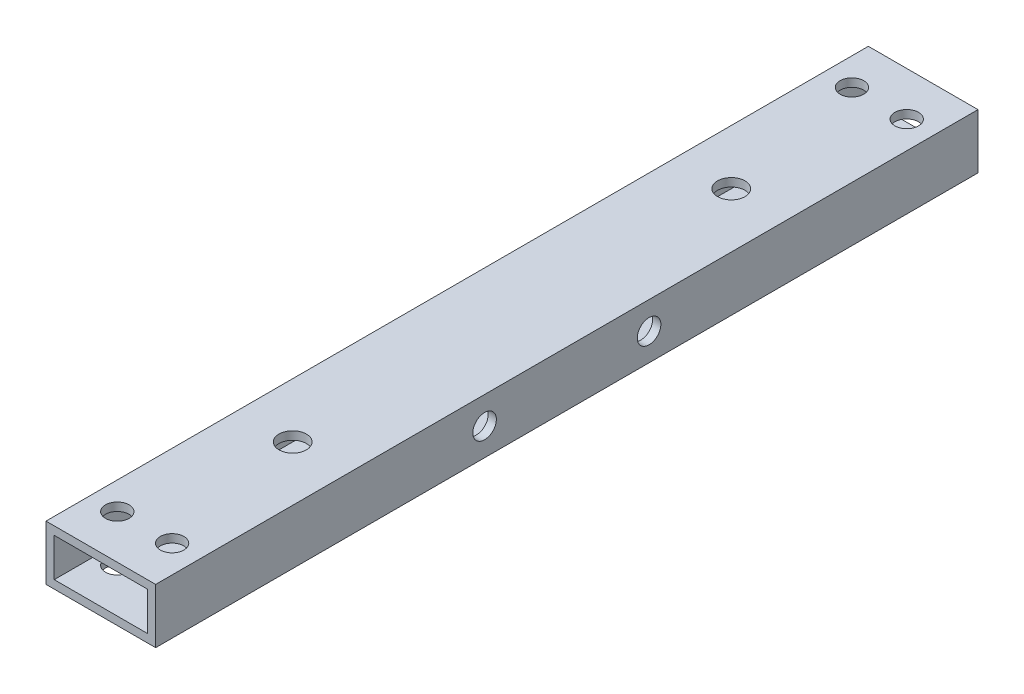
SolidWorks part; units mm, degrees
material "5052-H34"
ref_plane "正面" through (0, 0, 0) normal (0, 0, 1) x (1, 0, 0)
ref_plane "平面" through (0, 0, 0) normal (0, 1, 0) x (1, 0, 0)
ref_plane "右側面" through (0, 0, 0) normal (1, 0, 0) x (0, 0, -1)
sketch "ｽｹｯﾁ1" plane through (0, 0, 0) normal (0, 0, 1) x (1, 0, 0)
  line L1 (-10, 5) -> (10, 5)
  line L2 (-10, 5) -> (-10, -5)
  line L3 (-10, -5) -> (10, -5)
  line L4 (10, 5) -> (10, -5)
  line L5 (-10, 5) -> (10, -5) construction
  line L6 (-10, -5) -> (10, 5) construction
  point P0 (0, 0)
  dimension "D1" = 20
  dimension "D2" = 10
extrude "押し出し-薄板1" add sketch "ｽｹｯﾁ1" along normal blind 150 thin
sketch "ｽｹｯﾁ2" plane through (0, 5, 0) normal (0, 1, 0) x (1, 0, 0)
  line L0 (-10, -75) -> (10, -75) construction
  line L1 (-10, -150) -> (-10, 0) construction
  line L2 (10, -150) -> (10, 0) construction
  line L3 (0, -150) -> (0, -142) construction
  line L4 (10, -150) -> (-10, -150) construction
  line L5 (0, -142) -> (5, -142) construction
  line L6 (0, -75) -> (0, -35) construction
  circle A0 centre (5, -142) radius 2.15
  circle A1 centre (-5, -142) radius 2.15
  circle A2 centre (5, -8) radius 2.15
  circle A3 centre (-5, -8) radius 2.15
  circle A4 centre (0, -35) radius 2.5
  circle A5 centre (0, -115) radius 2.5
  dimension "D1" = 4.3
  dimension "D4" = 5
  dimension "D2" = 8
  dimension "D3" = 10
  dimension "D5" = 80
extrude "ｶｯﾄ - 押し出し1" cut sketch "ｽｹｯﾁ2" against normal through all
sketch "ｽｹｯﾁ3" plane through (10, 0, 0) normal (1, 0, 0) x (0, 0, -1)
  line L0 (-75, 5) -> (-75, -5) construction
  line L1 (-150, 5) -> (0, 5) construction
  line L2 (-150, -5) -> (0, -5) construction
  line L3 (-75, 0) -> (-60, 0) construction
  circle A0 centre (-60, 0) radius 2.15
  circle A1 centre (-90, 0) radius 2.15
  dimension "D2" = 4.3
  dimension "D1" = 30
extrude "ｶｯﾄ - 押し出し2" cut sketch "ｽｹｯﾁ3" against normal through all
